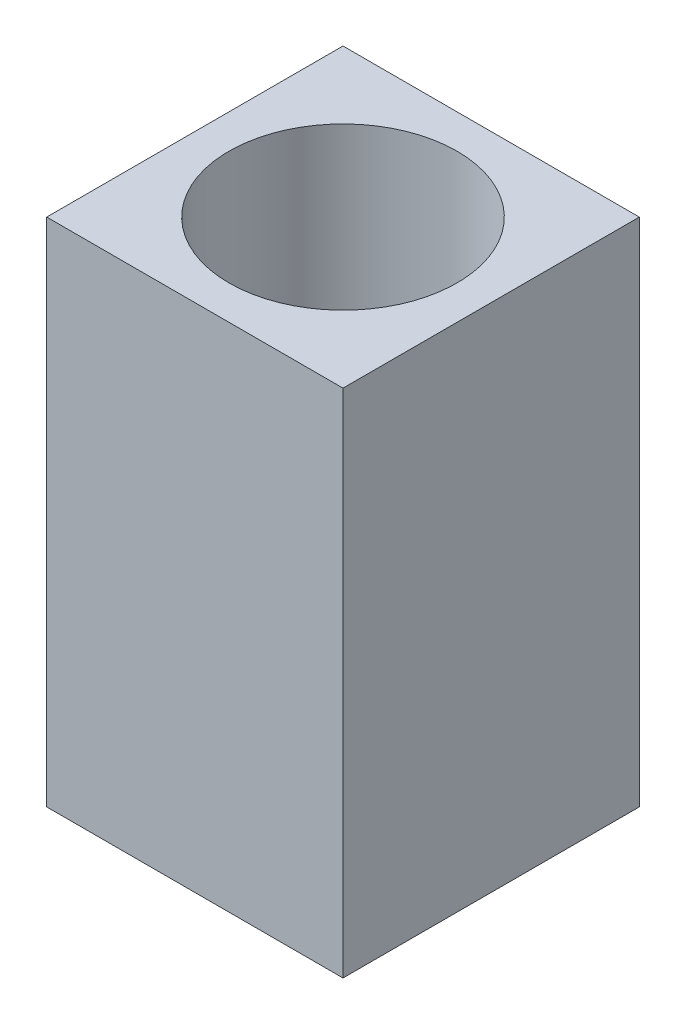
SolidWorks part; units mm, degrees
ref_plane "Front Plane" through (0, 0, 0) normal (0, 0, 1) x (1, 0, 0)
ref_plane "Top Plane" through (0, 0, 0) normal (0, 1, 0) x (1, 0, 0)
ref_plane "Right Plane" through (0, 0, 0) normal (1, 0, 0) x (0, 0, -1)
sketch "Sketch1" plane through (0, 0, 0) normal (0, 1, 0) x (1, 0, 0)
  line L1 (-17.4, 17.4) -> (17.4, 17.4)
  line L2 (-17.4, 17.4) -> (-17.4, -17.4)
  line L3 (-17.4, -17.4) -> (17.4, -17.4)
  line L4 (17.4, 17.4) -> (17.4, -17.4)
  line L5 (-17.4, 17.4) -> (17.4, -17.4) construction
  line L6 (-17.4, -17.4) -> (17.4, 17.4) construction
  circle A0 centre (0, 0) radius 13.4
  dimension "D1" = 26.8
  dimension "D2" = 34.8
  dimension "D3" = 34.8
extrude "Boss-Extrude1" add sketch "Sketch1" along normal blind 60
mirror "Mirror2"
